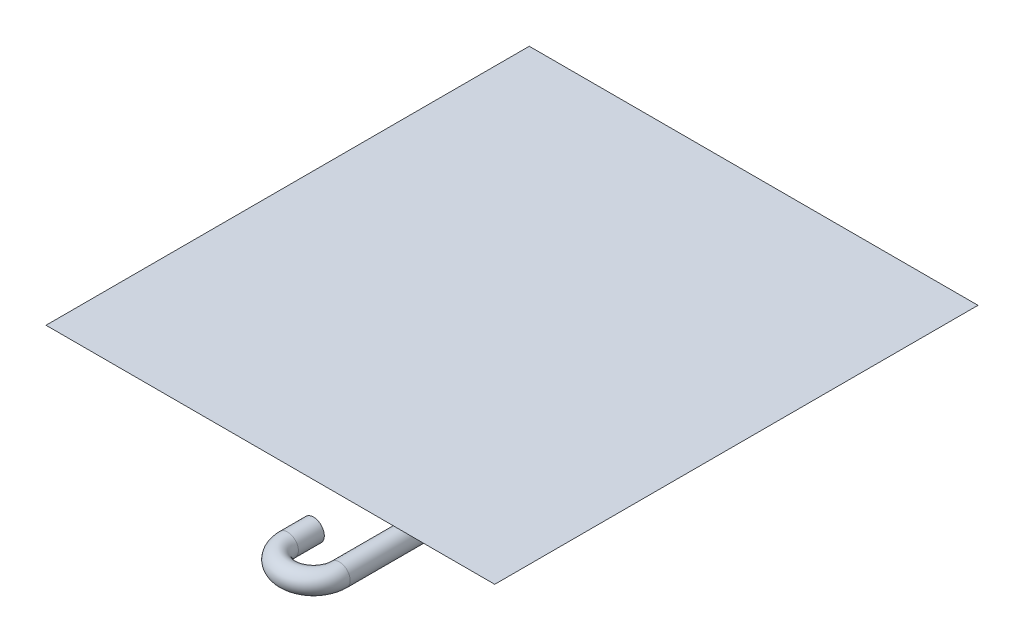
SolidWorks part; units mm, degrees
ref_plane "Front Plane" through (0, 0, 0) normal (0, 0, 1) x (1, 0, 0)
ref_plane "Top Plane" through (0, 0, 0) normal (0, 1, 0) x (1, 0, 0)
ref_plane "Right Plane" through (0, 0, 0) normal (1, 0, 0) x (0, 0, -1)
sketch "Sketch1" plane through (0, 0, 0) normal (0, 0, 1) x (1, 0, 0)
  line L0 (-82.55, 0) -> (82.55, 0)
  dimension "D1" = 165.1
surface "Surface-Extrude1" sketch "Sketch1" parameters "D1"=177.8
sketch "Sketch2" plane through (0, 0, 0) normal (0, 0, 1) x (1, 0, 0)
  line L0 (0, 0) -> (0, -50.8) construction
  circle A0 centre (0, -50.8) radius 3.9688
  dimension "D1" = 50.8
  dimension "D2" = 7.9375
extrude "Boss-Extrude1" add sketch "Sketch2" along normal mid plane 127
sketch "Sketch3" plane through (0, 0, 63.5) normal (0, 0, 1) x (1, 0, 0)
  circle A1 centre (0, -50.8) radius 3.9688
  circle A2 centre (0, -50.8) radius 3.9688
  dimension "D1" = 0
sketch "Sketch4" plane through (0, 0, 0) normal (0, 1, 0) x (1, 0, 0)
  line L0 (-3.9688, -63.5) -> (3.9688, -63.5) construction
  line L1 (-19.05, -63.5) -> (-19.05, -53.975)
  arc A0 (0, -63.5) -> (-19.05, -63.5) centre (-9.525, -63.5) cw
  dimension "D1" = 9.525
  dimension "D2" = 9.525
sweep "Sweep1" add profiles "Sketch3" path "Sketch4"
